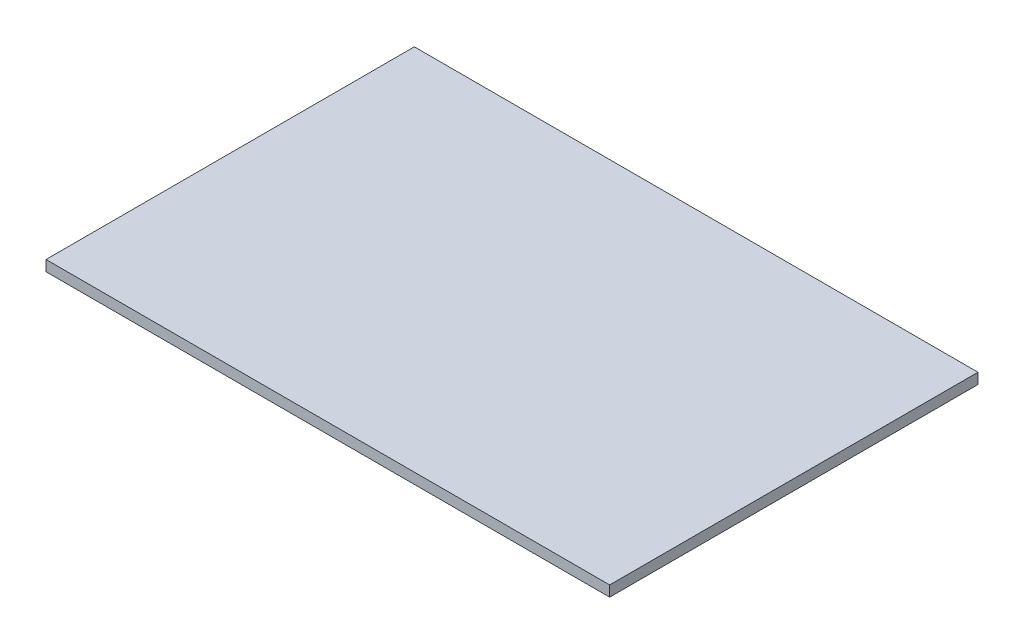
SolidWorks part; units mm, degrees
ref_plane "Front Plane" through (0, 0, 0) normal (0, 0, 1) x (1, 0, 0)
ref_plane "Top Plane" through (0, 0, 0) normal (0, 1, 0) x (1, 0, 0)
ref_plane "Right Plane" through (0, 0, 0) normal (1, 0, 0) x (0, 0, -1)
sketch "Sketch1" plane through (0, 0, 0) normal (0, 1, 0) x (1, 0, 0)
  line L1 (-41.783, -27.305) -> (41.783, -27.305)
  line L2 (-41.783, -27.305) -> (-41.783, 27.305)
  line L3 (-41.783, 27.305) -> (41.783, 27.305)
  line L4 (41.783, -27.305) -> (41.783, 27.305)
  line L5 (-41.783, -27.305) -> (41.783, 27.305) construction
  line L6 (-41.783, 27.305) -> (41.783, -27.305) construction
  point P0 (0, 0)
extrude "Boss-Extrude1" add sketch "Sketch1" along normal blind 1.5748
